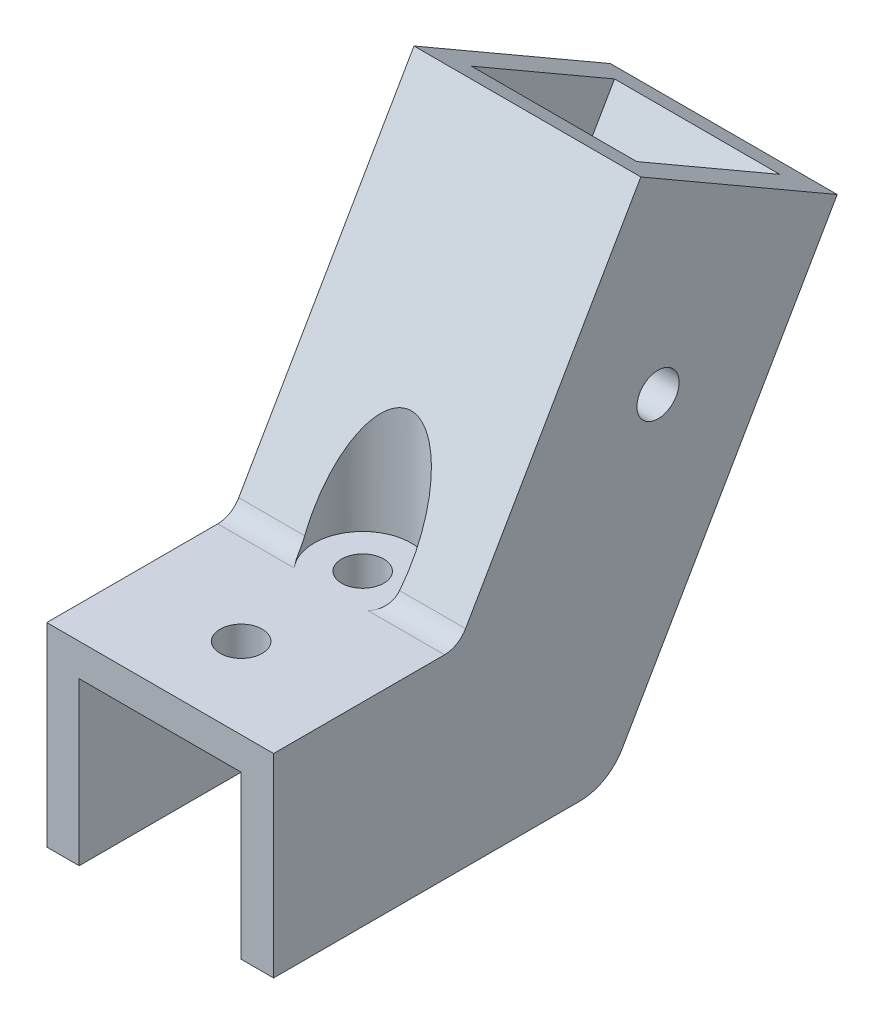
SolidWorks part; units mm, degrees
material "PA Type 6"
ref_plane "Front Plane" through (0, 0, 0) normal (0, 0, 1) x (1, 0, 0)
ref_plane "Top Plane" through (0, 0, 0) normal (0, 1, 0) x (1, 0, 0)
ref_plane "Right Plane" through (0, 0, 0) normal (1, 0, 0) x (0, 0, -1)
sketch "Sketch1" plane through (0, 0, 0) normal (1, 0, 0) x (0, 0, -1)
  line L0 (0, 0) -> (-24, 0)
  line L1 (-24, 0) -> (-24, -4)
  line L2 (-24, -4) -> (-4, -4)
  line L3 (-4, -4) -> (-4, -24)
  line L4 (-4, -24) -> (0, -24)
  line L5 (0, -24) -> (0, 0)
  dimension "D1" = 24
  dimension "D2" = 24
  dimension "D3" = 20
  dimension "D4" = 20
extrude "Boss-Extrude1" add sketch "Sketch1" along normal blind 28
sketch "Sketch2" plane through (28, 0, 0) normal (1, 0, 0) x (0, 0, -1)
  line L0 (0, 0) -> (19.8902, 34.4508) construction
  line L1 (0, 0) -> (19.1631, 0) construction
  line L2 (2.3094, -24) -> (30.5829, 24.9711)
  line L3 (-16.1658, 0) -> (6.3342, 38.9711)
  line L4 (0, -24) -> (2.3094, -24)
  line L5 (0, 0) -> (-24, 0) construction
  line L8 (0, -24) -> (0, 0)
  line L9 (0, 0) -> (-16.1658, 0)
  line L11 (6.3342, 38.9711) -> (30.5829, 24.9711)
  dimension "D1" = 60
  dimension "D4" = 45
  dimension "D2" = 14
  dimension "D3" = 14
extrude "Boss-Extrude2" add sketch "Sketch2" against normal blind 28
sketch "Sketch5" plane through (0, 31.9711, -18.4585) normal (0, 0.866, -0.5) x (1, 0, 0)
  line L0 (3.8, 10.2) -> (24.2, 10.2)
  line L1 (24.2, 10.2) -> (24.2, -10.2)
  line L2 (24.2, -10.2) -> (3.8, -10.2)
  line L3 (3.8, 10.2) -> (3.8, -10.2)
  line L4 (0, 14) -> (28, 14) construction
  line L5 (28, 14) -> (28, -14) construction
  line L6 (0, -14) -> (28, -14) construction
  line L7 (0, 14) -> (0, -14) construction
  dimension "D1" = 3.8
  dimension "D2" = 3.8
  dimension "D3" = 3.8
  dimension "D4" = 3.8
extrude "Cut-Extrude3" cut sketch "Sketch5" against normal blind 30
sketch "Sketch6" plane through (3.8, 0, 0) normal (1, 0, 0) x (0, 0, -1)
  line L0 (12.292, 0.8904) -> (3.4585, 5.9904)
  line L1 (12.292, 0.8904) -> (-5.3749, 11.0904) construction
  line L2 (3.4585, 5.9904) -> (3.4585, -14.4096)
  line L3 (3.4585, -14.4096) -> (12.292, 0.8904)
extrude "Cut-Extrude4" cut sketch "Sketch6" along normal blind 20.4
sketch "Sketch7" plane through (28, 0, 0) normal (1, 0, 0) x (0, 0, -1)
  line L0 (0, 0) -> (16.1784, 28.0218) construction
  line L1 (0, 0) -> (28.3839, 0) construction
  line L2 (30.5829, 24.9711) -> (6.3342, 38.9711) construction
  circle A0 centre (8.4585, 14.6506) radius 2.6
  dimension "D2" = 5.2
  dimension "D1" = 60
  dimension "D3" = 20
extrude "Cut-Extrude5" cut sketch "Sketch7" against normal through all
sketch "Sketch8" plane through (0, 0, 4) normal (0, 0, 1) x (1, 0, 0)
  line L0 (4, -4) -> (24, -4)
  line L1 (28, -4) -> (0, -4) construction
  line L2 (24, -4) -> (24, -24)
  line L3 (28, -24) -> (0, -24) construction
  line L4 (24, -24) -> (4, -24)
  line L5 (4, -24) -> (4, -4)
  line L6 (28, -4) -> (28, -24) construction
  line L7 (0, -4) -> (0, -24) construction
  dimension "D1" = 4
  dimension "D2" = 4
extrude "Cut-Extrude6" cut sketch "Sketch8" against normal through all
sketch "Sketch9" plane through (0, 0, 4) normal (0, 0, 1) x (1, 0, 0)
  line L0 (0, -4) -> (4, -4)
  line L1 (4, -4) -> (4, -24)
  line L2 (4, -24) -> (0, -24)
  line L3 (0, -24) -> (0, -4)
  line L4 (14, -4) -> (14, -17.6302) construction
  line L5 (28, -4) -> (0, -4) construction
  line L6 (24, -24) -> (28, -24)
  line L7 (24, -4) -> (24, -24)
  line L8 (28, -4) -> (24, -4)
  line L9 (28, -24) -> (28, -4)
extrude "Boss-Extrude3" add sketch "Sketch9" along normal blind 20
sketch "Sketch10" plane through (0, 0, 24) normal (0, 0, 1) x (1, 0, 0)
  line L0 (0, 0) -> (28, 0)
  line L1 (28, 0) -> (28, -24)
  line L2 (28, -24) -> (24, -24)
  line L3 (24, -24) -> (24, -4)
  line L4 (24, -4) -> (4, -4)
  line L5 (4, -4) -> (4, -24)
  line L6 (4, -24) -> (0, -24)
  line L7 (0, -24) -> (0, 0)
extrude "Boss-Extrude4" add sketch "Sketch10" along normal blind 15
sketch "Sketch11" plane through (0, -4, 0) normal (0, -1, 0) x (1, 0, 0)
  line L0 (14, 39) -> (14, 10.1433) construction
  line L1 (4, 39) -> (24, 39) construction
  circle A0 centre (14, 29) radius 2.6
  circle A1 centre (14, 14) radius 2.6
  dimension "D1" = 5.2
  dimension "D2" = 5.2
  dimension "D3" = 15
  dimension "D4" = 10
extrude "Cut-Extrude7" cut sketch "Sketch11" against normal through all
sketch "Sketch12" plane through (0, 0, 0) normal (0, 1, 0) x (1, 0, 0)
  circle A0 centre (14, -14) radius 6
  dimension "D1" = 12
extrude "Cut-Extrude8" cut sketch "Sketch12" along normal through all
fillet "Fillet1" radius 3 2 edges at (23.7977, 0, 16.1658) (4.2023, 0, 16.1658)
fillet "Fillet2" radius 6 2 edges at (2, -24, -2.3094) (26, -24, -2.3094)
